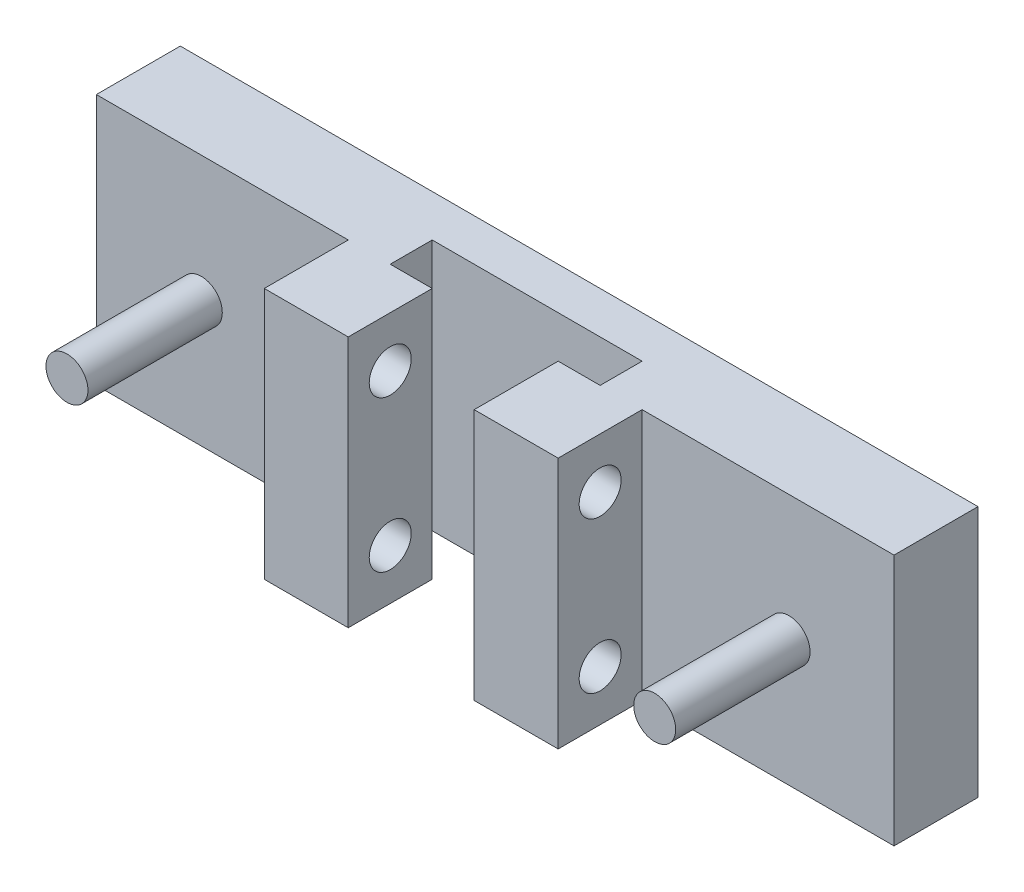
SolidWorks part; units mm, degrees
ref_plane "Front Plane" through (0, 0, 0) normal (0, 0, 1) x (1, 0, 0)
ref_plane "Top Plane" through (0, 0, 0) normal (0, 1, 0) x (1, 0, 0)
ref_plane "Right Plane" through (0, 0, 0) normal (1, 0, 0) x (0, 0, -1)
sketch "Sketch1" plane through (0, 0, 0) normal (0, 1, 0) x (1, 0, 0)
  line L0 (10, 0) -> (0, 0)
  line L1 (0, 0) -> (0, 20)
  line L2 (0, 20) -> (35, 20)
  line L3 (35, 20) -> (35, 0)
  line L4 (35, 0) -> (25, 0)
  line L5 (25, 0) -> (25, 10)
  line L6 (10, 10) -> (10, 0)
  line L7 (10, 10) -> (5, 10)
  line L8 (5, 10) -> (5, 15)
  line L9 (5, 15) -> (30, 15)
  line L10 (30, 15) -> (30, 10)
  line L11 (30, 10) -> (25, 10)
  line L13 (0, 20) -> (-30, 20)
  line L14 (0, 20) -> (0, 10)
  line L15 (0, 10) -> (-30, 10)
  line L16 (-30, 20) -> (-30, 10)
  line L17 (35, 20) -> (65, 20)
  line L18 (35, 20) -> (35, 10)
  line L19 (35, 10) -> (65, 10)
  line L20 (65, 20) -> (65, 10)
  dimension "D1" = 5
  dimension "D2" = 5
  dimension "D3" = 5
  dimension "D4" = 10
  dimension "D5" = 20
  dimension "D6" = 25
  dimension "D7" = 5
  dimension "D8" = 30
  dimension "D9" = 10
extrude "Boss-Extrude1" add sketch "Sketch1" along normal blind 30 contours L13 L16 L15 L1 | L10 L11 L5 L4 L3 L2 L1 L0 L6 L7 L8 L9 | L20 L17 L3 L19
sketch "Sketch2" plane through (10, 0, 0) normal (1, 0, 0) x (0, 0, -1)
  line L0 (0, 30) -> (0, 0) construction
  line L1 (10, 0) -> (0, 0) construction
  line L2 (10, 30) -> (0, 30) construction
  circle A0 centre (5, 24) radius 2.5
  circle A1 centre (5, 6) radius 2.5
  dimension "D1" = 5
  dimension "D2" = 5
  dimension "D3" = 5
  dimension "D4" = 5
  dimension "D5" = 6
  dimension "D6" = 6
extrude "Cut-Extrude1" cut sketch "Sketch2" against normal blind 22 and the other way blind 55
sketch "Sketch3" plane through (0, 0, -10) normal (0, 0, 1) x (1, 0, 0)
  line L0 (0, 0) -> (-30, 0) construction
  line L1 (0, 30) -> (0, 0) construction
  line L3 (35, 30) -> (35, 0) construction
  circle A0 centre (-17.5, 15) radius 2.5
  circle A1 centre (52.5, 15) radius 2.5
  dimension "D1" = 5
  dimension "D2" = 15
  dimension "D3" = 17.5
  dimension "D4" = 5
  dimension "D5" = 17.5
extrude "Boss-Extrude2" add sketch "Sketch3" along normal blind 16
